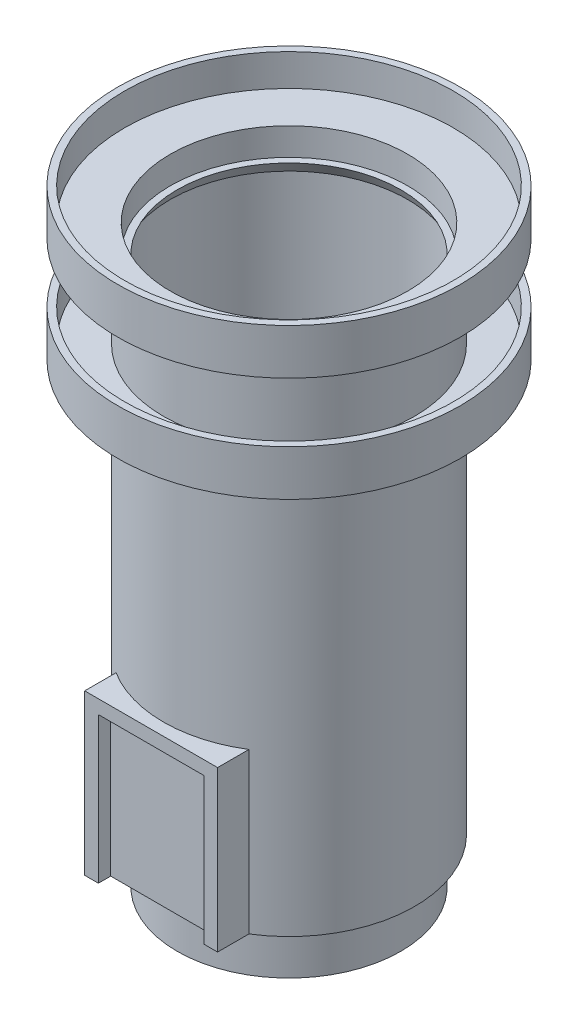
SolidWorks part; units mm, degrees
ref_plane "Alzado" through (0, 0, 0) normal (0, 0, 1) x (1, 0, 0)
ref_plane "Planta" through (0, 0, 0) normal (0, 1, 0) x (1, 0, 0)
ref_plane "Vista lateral" through (0, 0, 0) normal (1, 0, 0) x (0, 0, -1)
sketch "Croquis1" plane through (0, 0, 0) normal (0, 0, 1) x (1, 0, 0)
  line L0 (-17.713, 104.2623) -> (-17.713, 4.2623) construction
  line L1 (-40.713, 3.5199) -> (-40.713, 16.5199)
  line L2 (-40.713, 3.5199) -> (-42.213, 3.5199)
  line L3 (-42.213, 3.5199) -> (-42.213, 13.5199)
  line L4 (-42.213, 13.5199) -> (-45.213, 13.5199)
  line L5 (-45.213, 100.5199) -> (-45.213, 13.5199)
  line L6 (-40.713, 16.5199) -> (-43.713, 16.5199)
  line L8 (-45.213, 106.5199) -> (-45.213, 123.5199)
  line L9 (-55.213, 103.5199) -> (-55.213, 113.5199)
  line L10 (-55.213, 113.5199) -> (-53.713, 113.5199)
  line L11 (-53.713, 113.5199) -> (-53.713, 106.5199)
  line L12 (-53.713, 106.5199) -> (-45.213, 106.5199)
  line L13 (-45.213, 103.5199) -> (-45.213, 100.5199) construction
  line L14 (-55.213, 103.5199) -> (-45.213, 100.5199)
  line L17 (-55.213, 126.5199) -> (-45.213, 123.5199)
  line L18 (-55.213, 126.5199) -> (-55.213, 136.5199)
  line L19 (-55.213, 136.5199) -> (-53.713, 136.5199)
  line L20 (-53.713, 136.5199) -> (-53.713, 129.5199)
  line L21 (-53.713, 129.5199) -> (-43.713, 129.5199)
  line L22 (-45.213, 123.5199) -> (-42.213, 123.5199) construction
  line L23 (-43.713, 123.5199) -> (-42.213, 123.5199)
  line L24 (-43.713, 123.5199) -> (-43.713, 120.9176) construction
  line L25 (-42.213, 123.5199) -> (-43.713, 120.9176)
  line L26 (-43.713, 120.9176) -> (-43.713, 16.5199)
  line L27 (-43.713, 129.5199) -> (-43.713, 123.5199)
  dimension "D1" = 100
  dimension "D2" = 13
  dimension "D3" = 10
  dimension "D4" = 1.5
  dimension "D5" = 24.5
  dimension "D6" = 17
  dimension "D7" = 90
  dimension "D8" = 113
  dimension "D9" = 10
  dimension "D10" = 1.5
  dimension "D11" = 10
  dimension "D12" = 10
  dimension "D13" = 3
  dimension "D14" = 10
  dimension "D15" = 1.5
  dimension "D16" = 1.5
  dimension "D17" = 7
  dimension "D18" = 27.5
  dimension "D19" = 27.5
  dimension "D20" = 7
  dimension "D21" = 37.5
revolve "Revolución1" add sketch "Croquis1" angle 360 about L0
sketch "Croquis2" plane through (0, 13.5199, 0) normal (0, -1, 0) x (1, 0, 0)
  line L0 (-17.713, 27.5) -> (-17.713, 0) construction
  line L1 (-17.713, 23.3325) -> (-3.1582, 23.3325) construction
  line L3 (-32.2678, 23.3325) -> (-32.2678, 30.2025)
  line L4 (-3.1582, 23.3325) -> (-3.1582, 30.2025)
  line L5 (-32.2678, 30.2025) -> (-3.1582, 30.2025)
  circle A0 centre (-17.713, 0) radius 27.5 construction
  arc A1 (-32.2678, 23.3325) -> (-3.1582, 23.3325) centre (-17.713, 0) cw
  dimension "D1" = 6.87
  dimension "D2" = 6.87
extrude "Saliente-Extruir1" add sketch "Croquis2" against normal blind 35
sketch "Croquis3" plane through (0, 0, 30.2025) normal (0, 0, 1) x (1, 0, 0)
  line L0 (-3.1582, 13.5199) -> (-32.2678, 13.5199) construction
  line L1 (-29.2678, 13.5199) -> (-6.1582, 13.5199)
  line L2 (-29.2678, 13.5199) -> (-29.2678, 45.5199)
  line L3 (-29.2678, 45.5199) -> (-6.1582, 45.5199)
  line L4 (-6.1582, 13.5199) -> (-6.1582, 45.5199)
  line L5 (-3.1582, 48.5199) -> (-32.2678, 48.5199) construction
  line L6 (-32.2678, 48.5199) -> (-32.2678, 13.5199) construction
  line L7 (-3.1582, 48.5199) -> (-3.1582, 13.5199) construction
  dimension "D1" = 3
  dimension "D2" = 3
  dimension "D3" = 3
extrude "Cortar-Extruir1" cut sketch "Croquis3" against normal blind 2.7
